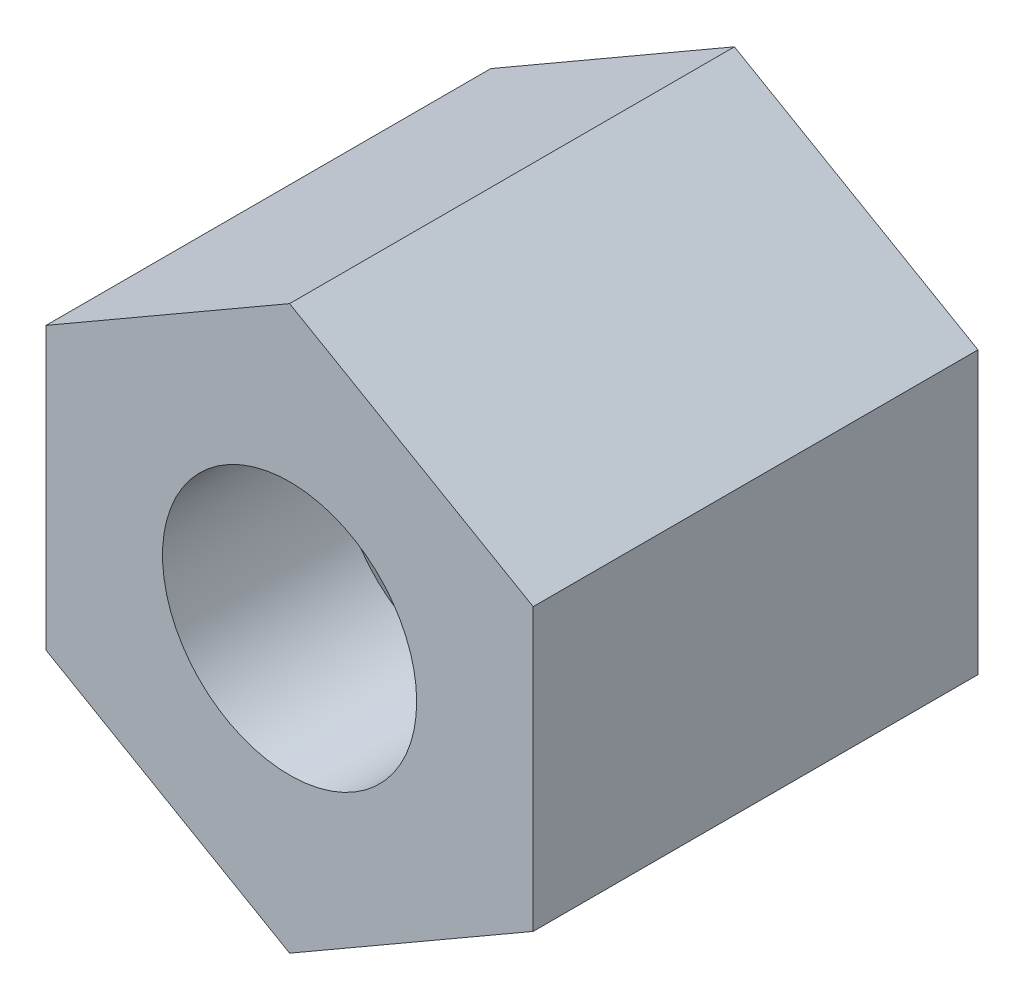
SolidWorks part; units mm, degrees
ref_plane "前视基准面" through (0, 0, 0) normal (0, 0, 1) x (1, 0, 0)
ref_plane "上视基准面" through (0, 0, 0) normal (0, 1, 0) x (1, 0, 0)
ref_plane "右视基准面" through (0, 0, 0) normal (1, 0, 0) x (0, 0, -1)
sketch "草图2" plane through (0, 0, 0) normal (0, 0, 1) x (1, 0, 0)
  line L0 (-1000, 0) -> (49000, 0) construction
  line L1 (0, 26.5581) -> (-23, 13.2791)
  line L2 (-23, 13.2791) -> (-23, -13.2791)
  line L3 (-23, -13.2791) -> (0, -26.5581)
  line L4 (0, -26.5581) -> (23, -13.2791)
  line L5 (23, -13.2791) -> (23, 13.2791)
  line L6 (23, 13.2791) -> (0, 26.5581)
  line L7 (0, -1000) -> (0, 49000) construction
  circle A0 centre (0, 0) radius 23 construction
  dimension "D1" = 46
  dimension "D2" = 53.1162
extrude "拉伸1" add sketch "草图2" along normal blind 42
sketch "草图12" plane through (0, 0, 0) normal (0, 0, -1) x (-1, 0, 0)
  circle A0 centre (0, 0) radius 15
  dimension "D1" = 30
extrude "拉伸3" cut sketch "草图12" against normal blind 20
sketch "草图16" plane through (0, 0, 20) normal (0, 0, -1) x (-1, 0, 0)
  circle A0 centre (0, 0) radius 15
  dimension "D1" = 30
extrude "拉伸6" cut sketch "草图16" against normal blind 4 draft 25
sketch "草图17" plane through (0, 0, 24) normal (0, 0, -1) x (-1, 0, 0)
  circle A0 centre (0, 0) radius 13.1348
  dimension "D1" = 26.2695
extrude "拉伸7" cut sketch "草图17" against normal blind 2 draft 40
sketch "草图18" plane through (0, 0, 42) normal (0, 0, 1) x (1, 0, 0)
  circle A0 centre (0, 0) radius 12
  dimension "D1" = 24
extrude "拉伸8" cut sketch "草图18" against normal blind 18
